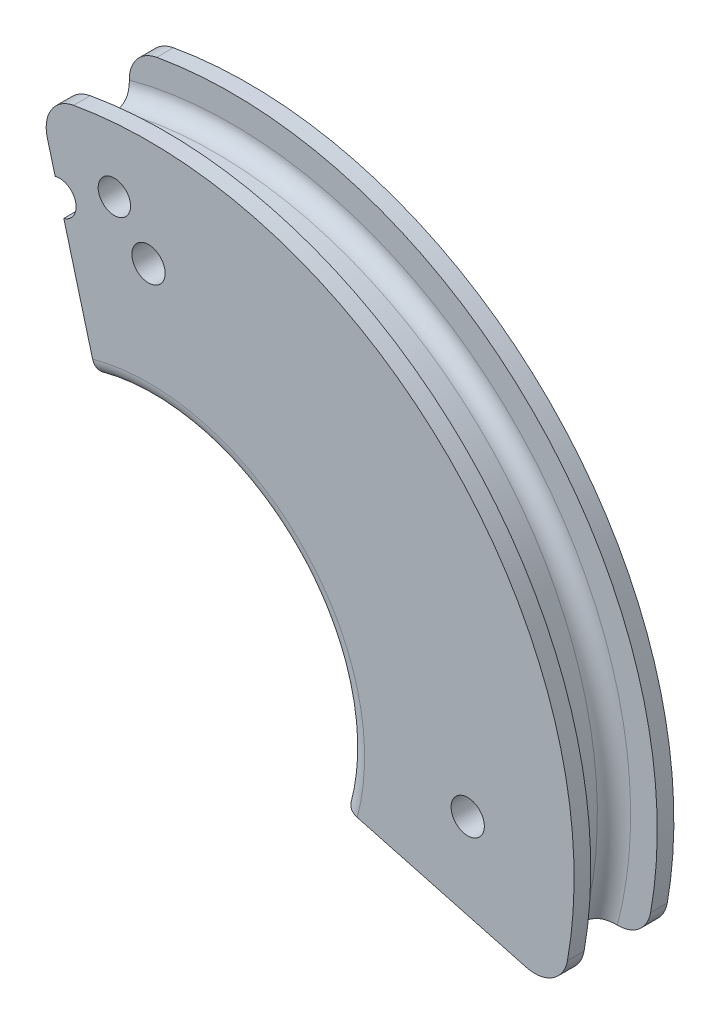
SolidWorks part; units mm, degrees
ref_plane "Front" through (0, 0, 0) normal (0, 0, 1) x (1, 0, 0)
ref_plane "Top" through (0, 0, 0) normal (0, 1, 0) x (1, 0, 0)
ref_plane "Right" through (0, 0, 0) normal (1, 0, 0) x (0, 0, -1)
sketch "Sketch1" plane through (0, 0, 0) normal (0, 0, 1) x (1, 0, 0)
  circle A2 centre (9.6, 0) radius 0.5
  circle A24 centre (0, 0) radius 12
  circle A25 centre (0, 0) radius 6
  circle A30 centre (0, -9.6) radius 0.5
  circle A32 centre (-9.6, 0) radius 0.5
  circle A34 centre (0, 9.6) radius 0.5
  point P20 (0, 0)
  dimension "D1" = 4
  dimension "D2" = 24
  dimension "D3" = 12
extrude "Boss-Extrude1" add sketch "Sketch1" along normal mid plane 3
sketch "Sketch2" plane through (0, 0, 0) normal (0, 1, 0) x (1, 0, 0)
  line L1 (0, 0) -> (0, 3.24) construction
  line L3 (-11.5, 0.5) -> (-11.5, -0.5)
  line L4 (-11.5, 0) -> (-12, 0) construction
  line L5 (-12, -1) -> (-12, 1)
  line L6 (-12, 1.5) -> (-12, -1.5) construction
  arc A1 (-12, 1) -> (-11.5, 0.5) centre (-12, 0.5) cw
  arc A2 (-12, -1) -> (-11.5, -0.5) centre (-12, -0.5) ccw
  dimension "D1" = 23
  dimension "D2" = 2
revolve "Cut-Revolve1" cut sketch "Sketch2" angle 360 about L1
sketch "Sketch6" plane through (0, 0, 0) normal (0, 1, 0) x (1, 0, 0)
  line L0 (0, 0) -> (15.0491, 0) construction
  line L1 (12, 1.5) -> (12.8, 1.5)
  line L2 (12, 1.5) -> (12, 1)
  line L3 (12, 1) -> (12.8, 1)
  line L4 (12.8, 1.5) -> (12.8, 1)
  line L5 (12.8, -1.5) -> (12.8, -1)
  line L6 (12, -1) -> (12.8, -1)
  line L7 (12, -1.5) -> (12, -1)
  line L8 (12, -1.5) -> (12.8, -1.5)
  line L9 (12, -1) -> (-12, -1) construction
  line L10 (0, 0) -> (0, 2.8804) construction
  arc A0 (11.5, -0.5) -> (12, -1) centre (12, -0.5) ccw construction
  dimension "D1" = 0.8
revolve "Revolve1" add sketch "Sketch6" angle 360 about L10
sketch "Sketch4" plane through (0, 0, 0) normal (0, 0, 1) x (1, 0, 0)
  line L0 (-3.7436, 13.9714) -> (0, 0)
  line L1 (0, 0) -> (8.4853, 8.4853) construction
  line L2 (0, 0) -> (-16.6927, 0) construction
  line L3 (14.9002, -3.9925) -> (0, 0)
  line L5 (-3.7436, 13.9714) -> (-15.1881, 13.9714)
  line L6 (-15.1881, 13.9714) -> (-15.1881, -14.8394)
  line L7 (-15.1881, -14.8394) -> (14.9002, -14.8394)
  line L10 (14.9002, -3.9925) -> (14.9002, -14.8394)
  point P15 (11.5911, -3.1058)
  point P18 (-3.1058, 11.5911)
  dimension "D3" = 60
  dimension "D1" = 135
  dimension "D2" = 120
extrude "Cut-Extrude1" cut sketch "Sketch4" against normal through all both and the other way through all
sketch "Sketch5" plane through (0, 0, 1.5) normal (0, 0, 1) x (1, 0, 0)
  line L0 (-1.5529, 5.7956) -> (-3.3129, 12.3639) construction
  circle A0 centre (-2.6769, 9.9902) radius 0.5
  circle A1 centre (-1.0268, 10.8291) radius 0.4873
  dimension "D1" = 1
extrude "Cut-Extrude2" cut sketch "Sketch5" against normal through all both and the other way through all
fillet "Fillet1" radius 0.5 2 edges at (4.2426, 4.2426, 1.5) (4.2426, 4.2426, -1.5)
fillet "Fillet2" radius 1 4 edges at (12.3639, -3.3129, -1.25) (12.3639, -3.3129, 1.25) (-3.3129, 12.3639, -1.25) (-3.3129, 12.3639, 1.25)
